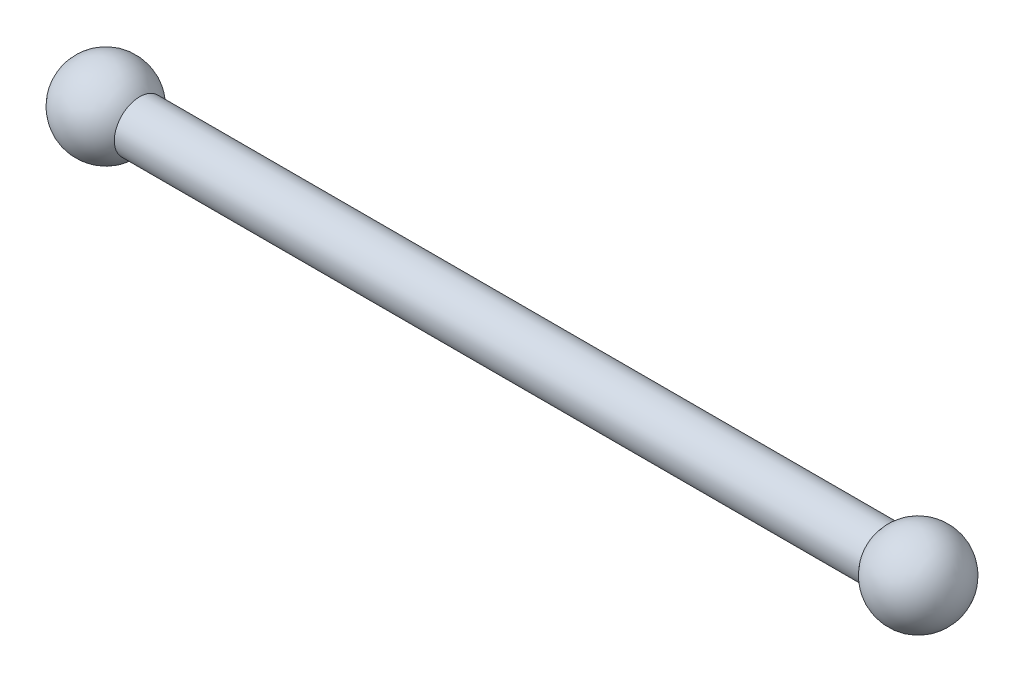
SolidWorks part; units mm, degrees
ref_plane "Front Plane" through (0, 0, 0) normal (0, 0, 1) x (1, 0, 0)
ref_plane "Top Plane" through (0, 0, 0) normal (0, 1, 0) x (1, 0, 0)
ref_plane "Right Plane" through (0, 0, 0) normal (1, 0, 0) x (0, 0, -1)
sketch "Sketch4" plane through (0, 0, 0) normal (1, 0, 0) x (0, 0, -1)
  line L0 (0, 0) -> (2.5, 0)
  line L1 (2.5, 0) -> (2.5, -2.5)
  arc A0 (0, 0) -> (2.5, -2.5) centre (2.5, 0) ccw
  dimension "D3" = 2.5
  dimension "D1" = 2.5
  dimension "D2" = 2.5
revolve "Semi-circle Revolve" add sketch "Sketch4" angle 360 about L1
mirror "Full-circle Mirror" about plane through (0, 0, 0) normal (0, -1, 0) of "Semi-circle Revolve"
sketch "Sketch5" plane through (0, 0, 0) normal (1, 0, 0) x (0, 0, -1)
  line L0 (0, 0) -> (2.5, 0) construction
  circle A0 centre (2.5, 0) radius 1.5
  dimension "D2" = 3
  dimension "D1" = 2.5
extrude "Shaft" add sketch "Sketch5" along normal blind 48
sketch "Sketch6" plane through (48, 0, 0) normal (1, 0, 0) x (0, 0, -1)
  line L0 (0, 0) -> (2.5, 0)
  line L1 (2.5, 0) -> (2.5, -2.5)
  arc A0 (0, 0) -> (2.5, -2.5) centre (2.5, 0) ccw
  dimension "D1" = 2.5
  dimension "D2" = 2.5
revolve "Opposite Semi-circle Revolve" add sketch "Sketch6" angle 360 about L1
mirror "Opposite Full-circle Mirror" about plane through (48, 0, 0) normal (0, 1, 0) of "Opposite Semi-circle Revolve"
